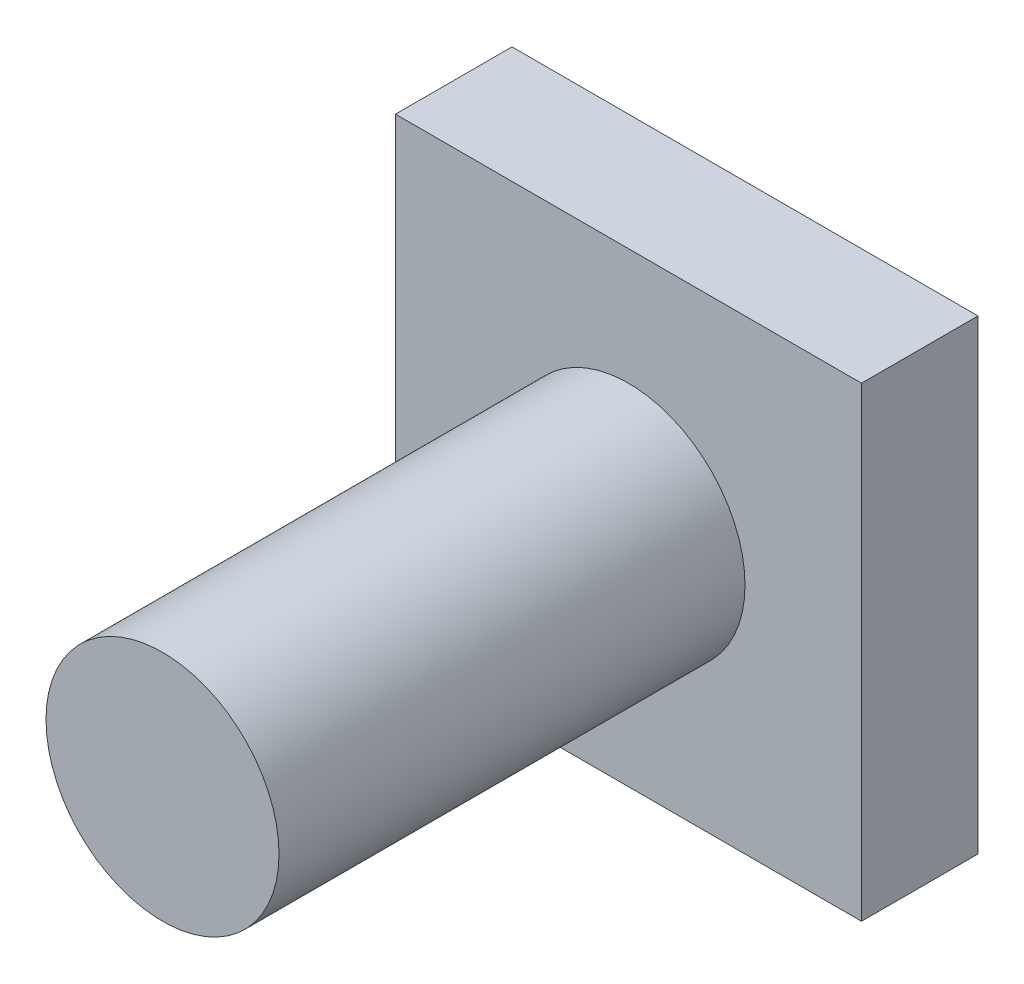
SolidWorks part; units mm, degrees
ref_plane "前视基准面" through (0, 0, 0) normal (0, 0, 1) x (1, 0, 0)
ref_plane "上视基准面" through (0, 0, 0) normal (0, 1, 0) x (1, 0, 0)
ref_plane "右视基准面" through (0, 0, 0) normal (1, 0, 0) x (0, 0, -1)
other "Configuration Table"
sketch "草图1" plane through (0, 0, 0) normal (0, 0, 1) x (1, 0, 0)
  circle A0 centre (0, 0) radius 5
  dimension "D1" = 10
extrude "凸台-拉伸1" add sketch "草图1" along normal mid plane 20
sketch "草图2" plane through (0, 0, -10) normal (0, 0, -1) x (-1, 0, 0)
  line L1 (-10, -10) -> (10, -10)
  line L2 (-10, -10) -> (-10, 10)
  line L3 (-10, 10) -> (10, 10)
  line L4 (10, -10) -> (10, 10)
  line L5 (-10, -10) -> (10, 10) construction
  line L6 (-10, 10) -> (10, -10) construction
  point P0 (0, 0)
  dimension "D1" = 20
  dimension "D2" = 20
extrude "凸台-拉伸2" add sketch "草图2" along normal blind 5
